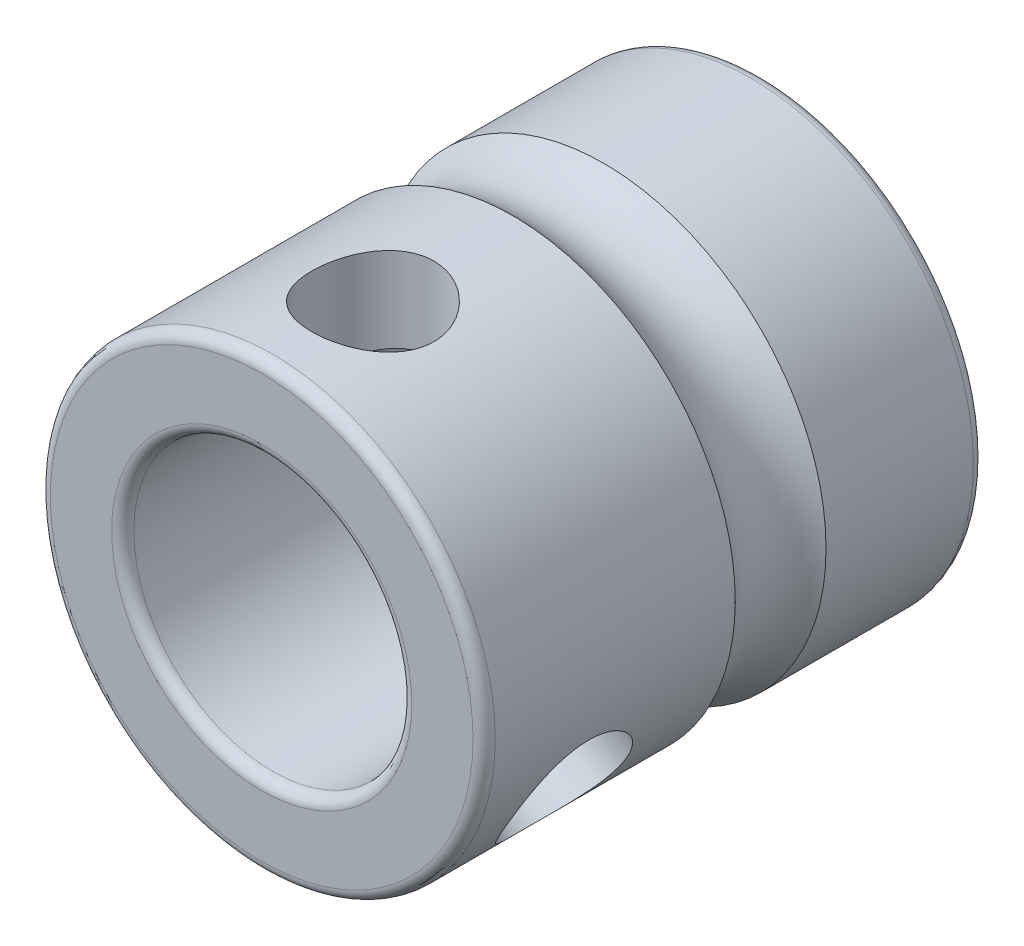
SolidWorks part; units mm, degrees
material "1.2083 (X40Cr14)"
ref_plane "Plan de face" through (0, 0, 0) normal (0, 0, 1) x (1, 0, 0)
ref_plane "Plan de dessus" through (0, 0, 0) normal (0, 1, 0) x (1, 0, 0)
ref_plane "Plan de droite" through (0, 0, 0) normal (1, 0, 0) x (0, 0, -1)
sketch "Esquisse1" plane through (0, 0, 0) normal (1, 0, 0) x (0, 0, -1)
  line L0 (2.4495, 12) -> (10.4, 12)
  line L1 (-2.4495, 0) -> (5.2289, 0) construction
  line L4 (-15.4, 12) -> (-2.4495, 12)
  line L5 (-16, 11.4) -> (-16, 8.1)
  line L6 (-15.4, 7.5) -> (10.4, 7.5)
  line L7 (11, 11.4) -> (11, 8.1)
  arc A0 (10.4, 7.5) -> (11, 8.1) centre (10.4, 8.1) ccw
  arc A1 (-2.4495, 12) -> (2.4495, 12) centre (0, 14.5) ccw
  arc A2 (10.4, 12) -> (11, 11.4) centre (10.4, 11.4) cw
  arc A3 (-16, 8.1) -> (-15.4, 7.5) centre (-15.4, 8.1) ccw
  arc A4 (-15.4, 12) -> (-16, 11.4) centre (-15.4, 11.4) ccw
  point P5 (-16, 7.5)
  point P12 (11, 7.5)
  dimension "D1" = 7.5
  dimension "D6" = 0.6
  dimension "D7" = 7
  dimension "D2" = 0.6
  dimension "D3" = 12
  dimension "D4" = 27
  dimension "D5" = 16
revolve "Révolution1" add sketch "Esquisse1" angle 360 about L1
hole_wizard "Dégagement M61" positions "Esquisse5" profile "Esquisse2" hole size "M6" standard "ISO"
sketch "Esquisse5" plane through (0, 0, 0) normal (0, 1, 0) x (1, 0, 0)
  line L0 (-11.4, -16) -> (11.4, -16) construction
  point P0 (0, -10)
  dimension "D1" = 6
sketch "Esquisse2" plane through (0, 0, 10) normal (1, 0, 0) x (0, 0, -1)
  line L0 (0, 0) -> (0, 16.3937)
  line L1 (0, 16.3937) -> (3.3, 16.3937)
  line L2 (3.3, 16.3937) -> (3.3, 0)
  line L5 (3.3, 0) -> (0, 0)
  line L11 (0, -6.35) -> (0, 107.95) construction
  dimension "Diamètre du perçage jusqu'au prochain" = 6.6
  dimension "Profondeur du perçage jusqu'au prochain" = 16.3937
pattern_circular "Répétition circulaire1" count 2 every 120 about axis through (0, 0, 2.4495) along (0, 0, 1) of "Dégagement M61"
